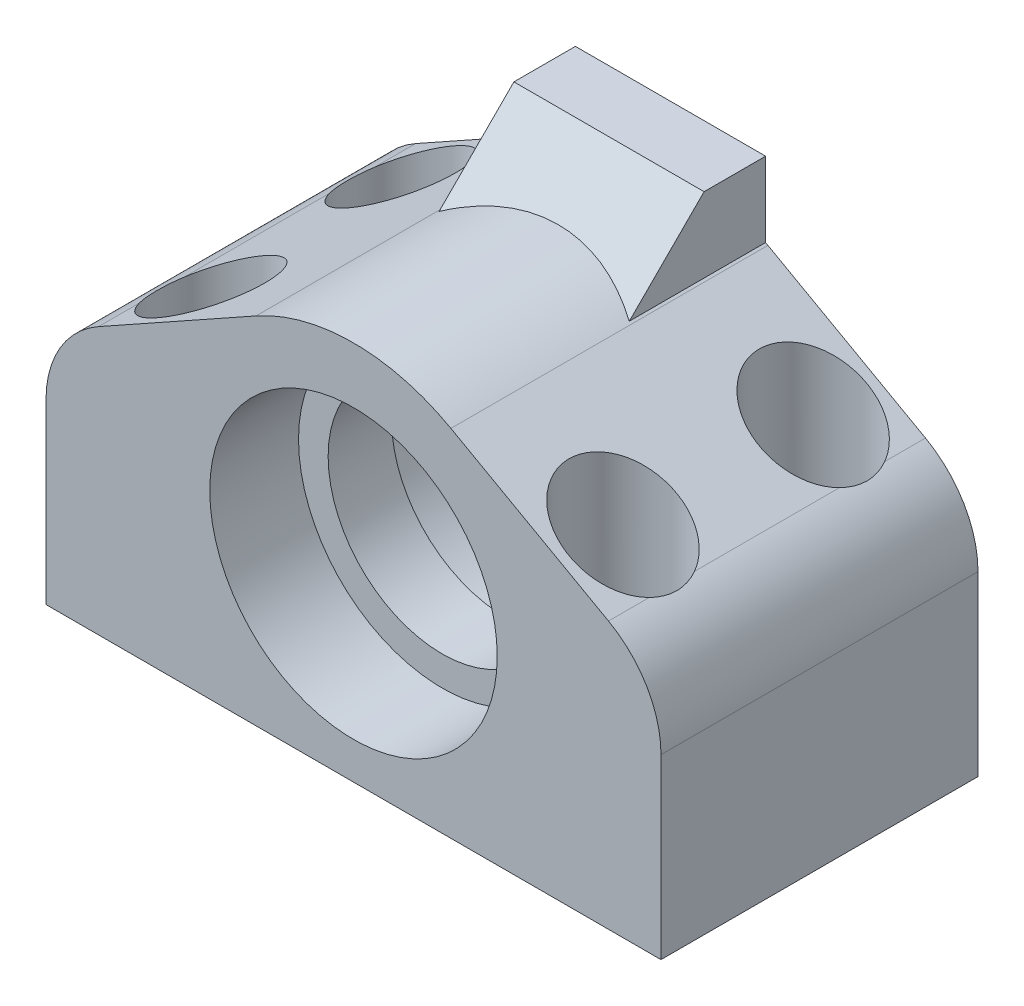
SolidWorks part; units mm, degrees
material "ABS"
ref_plane "Front Plane" through (0, 0, 0) normal (0, 0, 1) x (1, 0, 0)
ref_plane "Top Plane" through (0, 0, 0) normal (0, 1, 0) x (1, 0, 0)
ref_plane "Right Plane" through (0, 0, 0) normal (1, 0, 0) x (0, 0, -1)
sketch "Sketch1" plane through (0, 0, 0) normal (0, 0, 1) x (1, 0, 0)
  line L0 (0, 0) -> (0, 33.2505) construction
  line L2 (24.25, 4) -> (24.25, -10)
  line L3 (24.25, -10) -> (-24.25, -10)
  line L4 (-24.25, 4) -> (-24.25, -10)
  line L7 (-20.11, 11.0556) -> (-7.6823, 17.9994)
  line L8 (20.11, 11.0556) -> (7.6823, 17.9994)
  arc A0 (7.6823, 17.9994) -> (-7.6823, 17.9994) centre (0, 4.25) ccw
  arc A1 (20.11, 11.0556) -> (24.25, 4) centre (16.1678, 4) cw
  arc A2 (-20.11, 11.0556) -> (-24.25, 4) centre (-16.1678, 4) ccw
  circle A3 centre (0, 4.25) radius 9
  point P0 (0, 0)
  dimension "D2" = 31.5
  dimension "D3" = 30
  dimension "D4" = 14
  dimension "D9" = 18
  dimension "D1" = 48.5
  dimension "D5" = 4.14
  dimension "D6" = 4.14
  dimension "D7" = 14
  dimension "D8" = 10
extrude "Boss-Extrude1" add sketch "Sketch1" along normal blind 25
sketch "Sketch2" plane through (0, 0, 25) normal (0, 0, 1) x (1, 0, 0)
  circle A0 centre (0, 4.25) radius 11.335
  dimension "D1" = 22.67
extrude "Cut-Extrude1" cut sketch "Sketch2" against normal blind 7
sketch "Sketch3" plane through (0, 0, 0) normal (0, 0, -1) x (-1, 0, 0)
  circle A0 centre (0, 4.25) radius 11.335
  dimension "D1" = 22.67
extrude "Cut-Extrude2" cut sketch "Sketch3" against normal blind 13
sketch "Sketch4" plane through (0, 0, 0) normal (0, 0, -1) x (-1, 0, 0)
  line L0 (-7.5, 18.1012) -> (-7.5, 24)
  line L1 (-20.11, 11.0556) -> (-7.6823, 17.9994) construction
  line L2 (-7.5, 24) -> (7.5, 24)
  line L3 (7.5, 24) -> (7.5, 18.1012)
  line L4 (7.6823, 17.9994) -> (20.11, 11.0556) construction
  line L5 (24.25, -10) -> (-24.25, -10) construction
  arc A1 (7.5, 18.1012) -> (-7.5, 18.1012) centre (0, 4.25) ccw
  dimension "D1" = 34
  dimension "D3" = 7.5
extrude "Boss-Extrude2" add sketch "Sketch4" against normal blind 4.85 separate body
sketch "Sketch5" plane through (7.5, 0, 0) normal (1, 0, 0) x (0, 0, -1)
  line L0 (-4.85, 24) -> (-4.85, 18.1012)
  line L1 (-4.85, 18.1012) -> (-10.7488, 18.1012)
  line L2 (-10.7488, 18.1012) -> (-4.85, 24)
  dimension "D1" = 45
extrude "Boss-Extrude3" add sketch "Sketch5" against normal blind 15
sketch "Sketch6" plane through (0, -10, 0) normal (0, -1, 0) x (1, 0, 0)
  line L0 (0, 0) -> (0, 12.5) construction
  line L1 (16.25, 5) -> (-16.25, 5) construction
  line L2 (16.25, 5) -> (16.25, 20) construction
  line L3 (16.25, 20) -> (-16.25, 20) construction
  line L4 (-16.25, 5) -> (-16.25, 20) construction
  line L5 (16.25, 5) -> (-16.25, 20) construction
  line L6 (16.25, 20) -> (-16.25, 5) construction
  line L7 (-24.25, 25) -> (24.25, 25) construction
  line L8 (-24.25, 0) -> (24.25, 0) construction
  circle A0 centre (-16.25, 20) radius 2.25
  circle A1 centre (16.25, 20) radius 2.25
  circle A2 centre (16.25, 5) radius 2.25
  circle A3 centre (-16.25, 5) radius 2.25
  point P0 (0, 12.5)
  dimension "D4" = 4.5
  dimension "D5" = 4.5
  dimension "D6" = 4.5
  dimension "D7" = 4.5
  dimension "D1" = 5
  dimension "D2" = 32.5
  dimension "D3" = 5
extrude "Cut-Extrude3" cut sketch "Sketch6" against normal through all
ref_plane "Plane1" through (0, 0, 0) normal (0, -1, 0) x (-1, 0, 0)
sketch "Sketch7" plane through (0, 0, 0) normal (0, -1, 0) x (-1, 0, 0)
  circle A0 centre (16.25, -20) radius 4.25
  circle A1 centre (16.25, -5) radius 4.25
  circle A2 centre (-16.25, -5) radius 4.25
  circle A3 centre (-16.25, -20) radius 4.25
  dimension "D1" = 8.5
  dimension "D2" = 8.5
  dimension "D3" = 8.5
  dimension "D4" = 8.5
extrude "Cut-Extrude4" cut sketch "Sketch7" against normal through all
